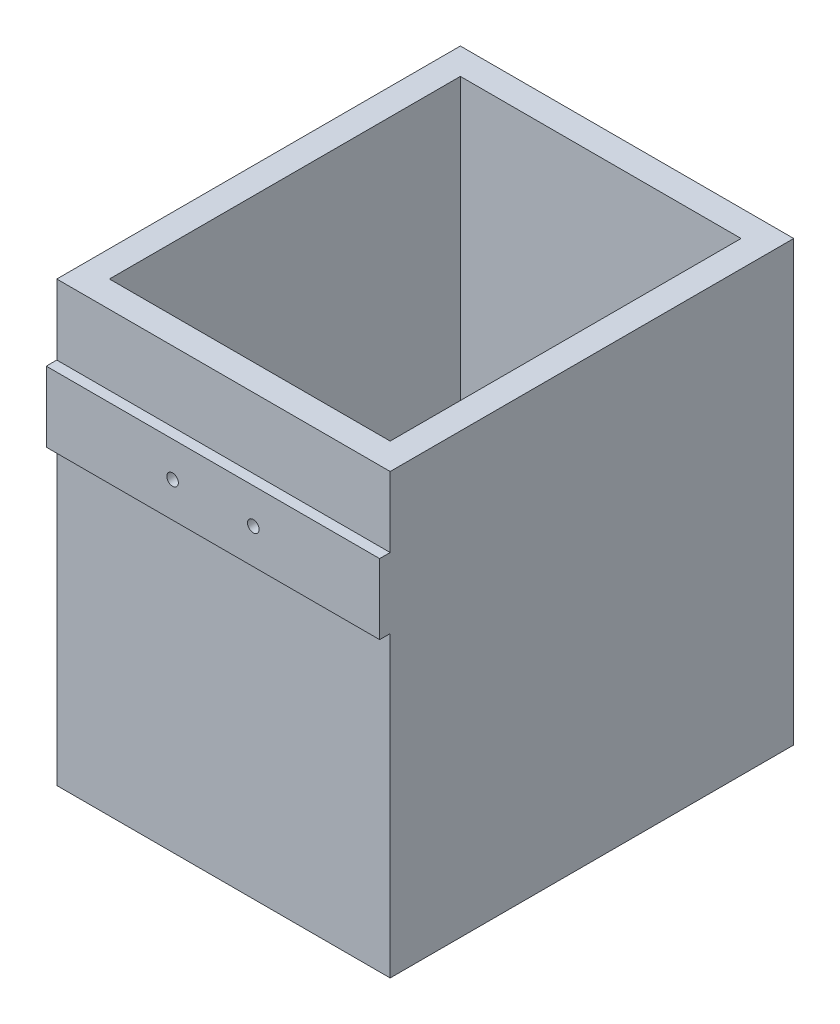
SolidWorks part; units mm, degrees
ref_plane "Front Plane" through (0, 0, 0) normal (0, 0, 1) x (1, 0, 0)
ref_plane "Top Plane" through (0, 0, 0) normal (0, 1, 0) x (1, 0, 0)
ref_plane "Right Plane" through (0, 0, 0) normal (1, 0, 0) x (0, 0, -1)
sketch "Sketch1" plane through (0, 0, 0) normal (0, 1, 0) x (1, 0, 0)
  line L1 (-40, -50) -> (40, -50)
  line L2 (-40, -50) -> (-40, 50)
  line L3 (-40, 50) -> (40, 50)
  line L4 (40, -50) -> (40, 50)
  line L5 (-40, -50) -> (40, 50) construction
  line L6 (-40, 50) -> (40, -50) construction
  point P0 (0, 0)
  dimension "D1" = 100
  dimension "D2" = 80
extrude "Boss-Extrude1" add sketch "Sketch1" along normal blind 9
sketch "Sketch2" plane through (0, 9, 0) normal (0, 1, 0) x (1, 0, 0)
  line L1 (-34, -42.7) -> (34, -42.7)
  line L2 (-34, -42.7) -> (-34, 42.7)
  line L3 (-34, 42.7) -> (34, 42.7)
  line L4 (34, -42.7) -> (34, 42.7)
  line L5 (-34, -42.7) -> (34, 42.7) construction
  line L6 (-34, 42.7) -> (34, -42.7) construction
  point P0 (0, 0)
  dimension "D1" = 85.4
  dimension "D2" = 68
extrude "Cut-Extrude1" cut sketch "Sketch2" against normal offset from surface (7 mm away) 2 contours L2 L1 L4 L3 up to face at (0, 0, 0)
sketch "Sketch3" plane through (0, 0, 0) normal (0, -1, 0) x (1, 0, 0)
  line L1 (-47.5, -57.5) -> (47.5, -57.5)
  line L2 (-47.5, -57.5) -> (-47.5, 57.5)
  line L3 (-47.5, 57.5) -> (47.5, 57.5)
  line L4 (47.5, -57.5) -> (47.5, 57.5)
  line L5 (-47.5, -57.5) -> (47.5, 57.5) construction
  line L6 (-47.5, 57.5) -> (47.5, -57.5) construction
  line L7 (-40, -50) -> (40, -50)
  line L8 (-40, -50) -> (-40, 50)
  line L9 (-40, 50) -> (40, 50)
  line L10 (40, -50) -> (40, 50)
  line L11 (-40, -50) -> (40, 50) construction
  line L12 (-40, 50) -> (40, -50) construction
  point P1 (0, 0)
  point P6 (0, 0)
  dimension "D1" = 115
  dimension "D2" = 95
extrude "Boss-Extrude2" add sketch "Sketch3" against normal blind 125
sketch "Sketch6" plane through (0, 0, 57.5) normal (0, 0, 1) x (1, 0, 0)
  line L0 (47.5, 125) -> (47.5, 0) construction
  line L1 (-47.5, 105) -> (47.5, 105)
  line L2 (-47.5, 105) -> (-47.5, 85)
  line L3 (-47.5, 85) -> (47.5, 85)
  line L4 (47.5, 105) -> (47.5, 85)
  line L5 (-47.5, 125) -> (-47.5, 0) construction
  line L6 (47.5, 125) -> (-47.5, 125) construction
  dimension "D1" = 20
  dimension "D2" = 20
extrude "Boss-Extrude4" add sketch "Sketch6" along normal blind 3
sketch "Sketch7" plane through (0, 0, 60.5) normal (0, 0, 1) x (1, 0, 0)
  line L0 (0, 0) -> (0, 125) construction
  line L1 (47.5, 125) -> (-47.5, 125) construction
  line L2 (-47.5, 95) -> (47.5, 95) construction
  line L3 (-47.5, 105) -> (-47.5, 85) construction
  line L4 (47.5, 85) -> (47.5, 105) construction
  circle A0 centre (-11.5, 95) radius 1.65
  circle A1 centre (11.5, 95) radius 1.65
  point P15 (9.85, 95)
  point P17 (-9.85, 95)
  dimension "D2" = 3.3
  dimension "D1" = 23
extrude "Cut-Extrude2" cut sketch "Sketch7" against normal up to surface (10.5 mm away) up to face at (0, 67, 50)
sketch "Sketch9" plane through (0, 0, 50) normal (0, 0, -1) x (-1, 0, 0)
  circle A0 centre (-11.5, 95) radius 3
  circle A1 centre (11.5, 95) radius 3
  circle A2 centre (-11.5, 95) radius 1.65 construction
  circle A3 centre (11.5, 95) radius 1.65 construction
  dimension "D1" = 6
extrude "Cut-Extrude3" cut sketch "Sketch9" against normal blind 3.2
